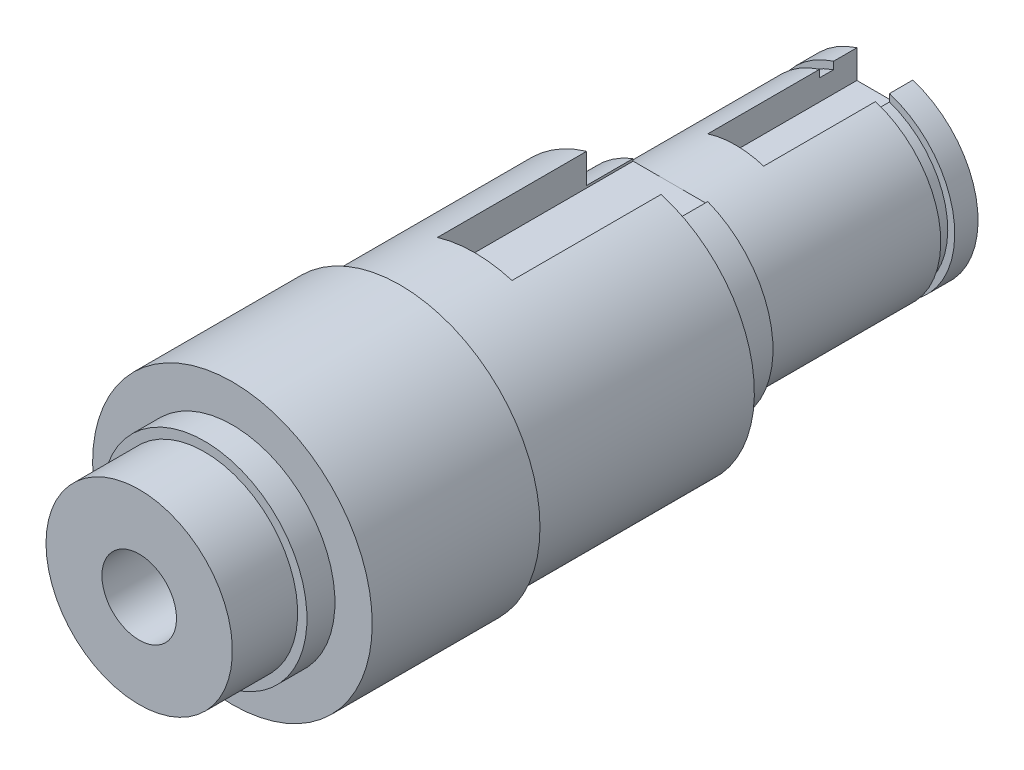
SolidWorks part; units mm, degrees
ref_plane "Front Plane" through (0, 0, 0) normal (0, 0, 1) x (1, 0, 0)
ref_plane "Top Plane" through (0, 0, 0) normal (0, 1, 0) x (1, 0, 0)
ref_plane "Right Plane" through (0, 0, 0) normal (1, 0, 0) x (0, 0, -1)
sketch "Sketch1" plane through (0, 0, 0) normal (0, 1, 0) x (1, 0, 0)
  line L0 (0, 122.7794) -> (0, -28.7468) construction
  line L1 (-40.845, 0) -> (48.845, 0) construction
  line L2 (4, 0) -> (10, 0)
  line L3 (10, 0) -> (10, 7)
  line L4 (11, 10) -> (15, 10)
  line L5 (15, 10) -> (15, 28)
  line L6 (14, 52) -> (11, 52)
  line L7 (10, 57) -> (10, 80)
  line L8 (10, 80) -> (4, 80)
  line L9 (4, 80) -> (4, 0)
  line L10 (11, 10) -> (11, 7)
  line L11 (11, 7) -> (10, 7)
  line L12 (14, 52) -> (14, 28)
  line L13 (14, 28) -> (15, 28)
  line L14 (11, 52) -> (11, 57)
  line L15 (11, 57) -> (10, 57)
  dimension "D1" = 10
  dimension "D2" = 80
  dimension "D3" = 10
  dimension "D4" = 52
  dimension "D5" = 15
  dimension "D6" = 10
  dimension "D7" = 4
  dimension "D8" = 11
  dimension "D9" = 7
  dimension "D10" = 28
  dimension "D11" = 14
  dimension "D12" = 57
  dimension "D13" = 11
revolve "Revolve1" add sketch "Sketch1" angle 360 about L0
sketch "Sketch2" plane through (0, 0, -52) normal (0, 0, -1) x (-1, 0, 0)
  line L0 (6.7175, 6.7175) -> (7.7782, 7.7782)
  line L1 (-25.9658, 0) -> (29.8373, 0) construction
  line L2 (8.2485, 4.713) -> (9.3424, 5.8069)
  line L3 (4.713, 8.2485) -> (5.8069, 9.3424)
  line L4 (1.7678, -1.7678) -> (15.0641, 11.5286) construction
  line L5 (-1.7678, 1.7678) -> (11.5286, 15.0641) construction
  line L6 (0, 0) -> (13.2964, 13.2964) construction
  line L7 (9.1652, -2.5) -> (10.7121, -2.5)
  line L8 (9.5, 0) -> (11, 0)
  line L9 (9.1652, 2.5) -> (10.7121, 2.5)
  line L10 (4.713, -8.2485) -> (5.8069, -9.3424)
  line L11 (6.7175, -6.7175) -> (7.7782, -7.7782)
  line L12 (8.2485, -4.713) -> (9.3424, -5.8069)
  line L13 (-2.5, -9.1652) -> (-2.5, -10.7121)
  line L14 (0, -9.5) -> (0, -11)
  line L15 (2.5, -9.1652) -> (2.5, -10.7121)
  line L16 (-8.2485, -4.713) -> (-9.3424, -5.8069)
  line L17 (-6.7175, -6.7175) -> (-7.7782, -7.7782)
  line L18 (-4.713, -8.2485) -> (-5.8069, -9.3424)
  line L19 (-9.1652, 2.5) -> (-10.7121, 2.5)
  line L20 (-9.5, 0) -> (-11, 0)
  line L21 (-9.1652, -2.5) -> (-10.7121, -2.5)
  line L22 (-4.713, 8.2485) -> (-5.8069, 9.3424)
  line L23 (-6.7175, 6.7175) -> (-7.7782, 7.7782)
  line L24 (-8.2485, 4.713) -> (-9.3424, 5.8069)
  line L25 (2.5, 9.1652) -> (2.5, 10.7121)
  line L26 (0, 9.5) -> (0, 11)
  line L27 (-2.5, 9.1652) -> (-2.5, 10.7121)
  circle A0 centre (0, 0) radius 11
  circle A1 centre (0, 0) radius 9.5
  point P62 (0, 0)
  dimension "D1" = 22
  dimension "D2" = 19
  dimension "D3" = 45
  dimension "D4" = 2.5
  dimension "D5" = 2.5
  dimension "D6" = 8
extrude "Cut-Extrude1" [suppressed] cut sketch "Sketch2" against normal blind 20
sketch "Sketch4" plane through (0, 0, -80) normal (0, 0, -1) x (-1, 0, 0)
  line L0 (-18.1547, 0) -> (20.785, 0) construction
  line L1 (9.8995, 9.8995) -> (10.6066, 10.6066)
  line L2 (10.9032, 8.7818) -> (11.6141, 9.4928)
  line L3 (8.7818, 10.9032) -> (9.4928, 11.6141)
  line L4 (1.0607, -1.0607) -> (14.4539, 12.3326) construction
  line L5 (-1.0607, 1.0607) -> (12.3326, 14.4539) construction
  line L6 (0, 0) -> (13.3932, 13.3932) construction
  line L7 (13.9194, -1.5) -> (14.9248, -1.5)
  line L8 (14, 0) -> (15, 0)
  line L9 (13.9194, 1.5) -> (14.9248, 1.5)
  line L10 (8.7818, -10.9032) -> (9.4928, -11.6141)
  line L11 (9.8995, -9.8995) -> (10.6066, -10.6066)
  line L12 (10.9032, -8.7818) -> (11.6141, -9.4928)
  line L13 (-1.5, -13.9194) -> (-1.5, -14.9248)
  line L14 (0, -14) -> (0, -15)
  line L15 (1.5, -13.9194) -> (1.5, -14.9248)
  line L16 (-10.9032, -8.7818) -> (-11.6141, -9.4928)
  line L17 (-9.8995, -9.8995) -> (-10.6066, -10.6066)
  line L18 (-8.7818, -10.9032) -> (-9.4928, -11.6141)
  line L19 (-13.9194, 1.5) -> (-14.9248, 1.5)
  line L20 (-14, 0) -> (-15, 0)
  line L21 (-13.9194, -1.5) -> (-14.9248, -1.5)
  line L22 (-8.7818, 10.9032) -> (-9.4928, 11.6141)
  line L23 (-9.8995, 9.8995) -> (-10.6066, 10.6066)
  line L24 (-10.9032, 8.7818) -> (-11.6141, 9.4928)
  line L25 (1.5, 13.9194) -> (1.5, 14.9248)
  line L26 (0, 14) -> (0, 15)
  line L27 (-1.5, 13.9194) -> (-1.5, 14.9248)
  circle A0 centre (0, 0) radius 15
  circle A1 centre (0, 0) radius 14
  point P61 (0, 0)
  circle M6 centre (0, 0) radius 10
  dimension "D3" = 45
  dimension "D6" = 8
  dimension "D1" = 30
  dimension "D2" = 28
  dimension "D4" = 1.5
extrude "Cut-Extrude2" [suppressed] cut sketch "Sketch4" against normal blind 20 contours A1 L27 L22 M6 | A1 L3 L25 M6 | A1 L9 L2 M6 | A1 L12 L7 M6 | A1 L15 L10 M6 | A1 L18 L13 M6 | A1 L21 L16 M6 | A1 L24 L19 M6
sketch "Sketch5" plane through (0, 0, -52) normal (0, 0, -1) x (-1, 0, 0)
  line L0 (-22.7421, 0) -> (22.7421, 0) construction
  line L1 (0, 17.4954) -> (0, -25.7444) construction
  line L2 (-11.1031, 14) -> (9.7265, 14) construction
  line L3 (-4, 18) -> (4, 18) construction
  line L4 (-4, 18) -> (-4, 10) construction
  line L5 (-4, 10) -> (4, 10) construction
  line L6 (4, 18) -> (4, 10) construction
  line L7 (-4, 10) -> (4, 10)
  line L8 (4, 10) -> (4, 13.4164)
  line L9 (-4, 10) -> (-4, 13.4164)
  circle A0 centre (0, 0) radius 14
  point P13 (0, 14)
  circle M16 centre (0, 0) radius 14
  circle M17 centre (0, 0) radius 11
  dimension "D1" = 28
  dimension "D2" = 8
  dimension "D3" = 8
  dimension "D4" = 4
  dimension "D5" = 4
extrude "Cut-Extrude3" cut sketch "Sketch5" against normal blind 16 and the other way blind 10 contours L9 L7 L8 M17 | L9 L8 M17 M16
sketch "Sketch6" plane through (0, 0, -80) normal (0, 0, -1) x (-1, 0, 0)
  line L0 (-17.6239, 0) -> (20.8513, 0) construction
  line L1 (0, -14.1242) -> (0, 18.9644) construction
  line L2 (-6.0225, 10) -> (9.4166, 10) construction
  line L3 (-3, 12.5) -> (3, 12.5) construction
  line L4 (-3, 12.5) -> (-3, 6.5) construction
  line L5 (-3, 6.5) -> (3, 6.5) construction
  line L6 (3, 12.5) -> (3, 6.5) construction
  line L7 (-3, 6.5) -> (3, 6.5)
  line L8 (3, 6.5) -> (3, 9.5394)
  line L9 (-3, 6.5) -> (-3, 9.5394)
  circle A0 centre (0, 0) radius 10
  point P11 (0, 10)
  dimension "D1" = 20
  dimension "D2" = 6
  dimension "D3" = 3
  dimension "D4" = 6
  dimension "D5" = 3.5
extrude "Cut-Extrude4" cut sketch "Sketch6" against normal blind 16
sketch "Sketch7" plane through (0, 0, 0) normal (0, 1, 0) x (1, 0, 0)
  line L0 (0, -11.7842) -> (0, 95.1927) construction
  line L1 (-18.4028, 0) -> (16.3105, 0) construction
  line L2 (9.25, 77.5) -> (10, 77.5)
  line L3 (9.25, 77.5) -> (9.25, 76)
  line L4 (9.25, 76) -> (10, 76)
  line L5 (10, 77.5) -> (10, 76)
  dimension "D1" = 10
  dimension "D4" = 1.5
  dimension "D2" = 9.25
  dimension "D3" = 76
revolve "Cut-Revolve1" cut sketch "Sketch7" angle 360 about L0
equation "\"shaftA_length\" = 80"
equation "\"D2@Sketch1\"=\"shaftA_length\""
equation "\"shaftA_lengthA\"= 7"
equation "\"D3@Sketch1\"=\"shaftA_lengthB\""
equation "\"shaftA_lengthB\"= 10"
equation "\"shaftA_lengthC\"= 28"
equation "\"shaftA_lengthD\"=52"
equation "\"D4@Sketch1\"=\"shaftA_lengthD\""
equation "\"shaftA_odB\"=22"
equation "\"D1@Sketch2\"=\"shaftA_odB\""
equation "\"shaftA_odA\"=20"
equation "\"D2@Sketch2\"=\"shaftA_odB\"-2*\"shaftA_splineB_depth\""
equation "\"D1@Sketch1\"=\"shaftA_odA\"/2"
equation "\"D5@Sketch1\"=\"shaftA_odC\"/2"
equation "\"shaftA_odC\"= 30"
equation "\"shaftA_odD\"= 28"
equation "\"shaftA_odE\"=22"
equation "\"shaftA_odF\"=20"
equation "\"D6@Sketch1\"=\"shaftA_odF\"/2"
equation "\"shaftA_splineB_width\"= 5"
equation "\"D4@Sketch2\"=\"shaftA_splineB_width\"/2"
equation "\"D5@Sketch2\"=\"shaftA_splineB_width\"/2"
equation "\"shaftA_splineB_depth\"= 1.5"
equation "\"shaftA_splineB_length\"=20"
equation "\"D1@Cut-Extrude1\"=\"shaftA_splineB_length\""
equation "\"shaftA_idA\"=8"
equation "\"D7@Sketch1\"=\"shaftA_idA\"/2"
equation "\"D1@Sketch4\"=\"shaftA_odC\""
equation "\"D2@Sketch4\"=\"shaftA_odC\"-2*\"shaftA_splineC_depth\""
equation "\"shaftA_splineC_width\"= 3"
equation "\"shaftA_splineC_depth\"= 1"
equation "\"shaftA_splineC_length\"= 10"
equation "\"D4@Sketch4\"=\"shaftA_splineC_width\"/2"
equation "\"D5@Sketch4\"=\"shaftA_splineC_width\"/2"
equation "\"D1@Sketch5\"=\"shaftA_odD\""
equation "\"shaftA_keywayD_b1\"=8"
equation "\"D2@Sketch5\"=\"shaftA_keywayD_b1\""
equation "\"shaftA_keywayD_h\"=8"
equation "\"D3@Sketch5\"=\"shaftA_keywayD_h\""
equation "\"shaftA_keywayD_t1\"=4"
equation "\"D4@Sketch5\"=\"shaftA_keywayD_t1\""
equation "\"D5@Sketch5\"=\"shaftA_keywayD_b1\"/2"
equation "\"shaftA_keywayD_l\"= 16"
equation "\"D1@Cut-Extrude3\"=\"shaftA_keywayD_l\""
equation "\"D1@Sketch6\"=\"shaftA_odF\""
equation "\"shaftA_keywayE_b1\"= 6"
equation "\"D2@Sketch6\"=\"shaftA_keywayE_b1\""
equation "\"D3@Sketch6\"=\"shaftA_keywayE_b1\"/2"
equation "\"shaftA_keywayE_h\"= 6"
equation "\"D4@Sketch6\"=\"shaftA_keywayE_h\""
equation "\"shaftA_keywayE_t1\"=3.5"
equation "\"D5@Sketch6\"=\"shaftA_keywayE_t1\""
equation "\"shaftA_keywayE_l\"=16"
equation "\"D1@Cut-Extrude4\"=\"shaftA_keywayE_l\""
equation "\"D8@Sketch1\"=\"shaftA_odB\"/2"
equation "\"D9@Sketch1\"=\"shaftA_lengthA\""
equation "\"D10@Sketch1\"=\"shaftA_lengthC\""
equation "\"D11@Sketch1\"=\"shaftA_odD\"/2"
equation "\"shaftA_lengthE\"= 57"
equation "\"D12@Sketch1\"=\"shaftA_lengthE\""
equation "\"D13@Sketch1\"=\"shaftA_odE\"/2"
equation "\"D1@Sketch7\"=\"shaftA_odF\"/2"
equation "\"shaftA_retaining_groove_od\"=18.5"
equation "\"D2@Sketch7\"=\"shaftA_retaining_groove_od\"/2"
equation "\"shaftA_retaining_groove_posZ\"= 76"
equation "\"D3@Sketch7\"=\"shaftA_retaining_groove_posZ\""
equation "\"shaftA_retaining_groove_length\"=1.5"
equation "\"D4@Sketch7\"=\"shaftA_retaining_groove_length\""
